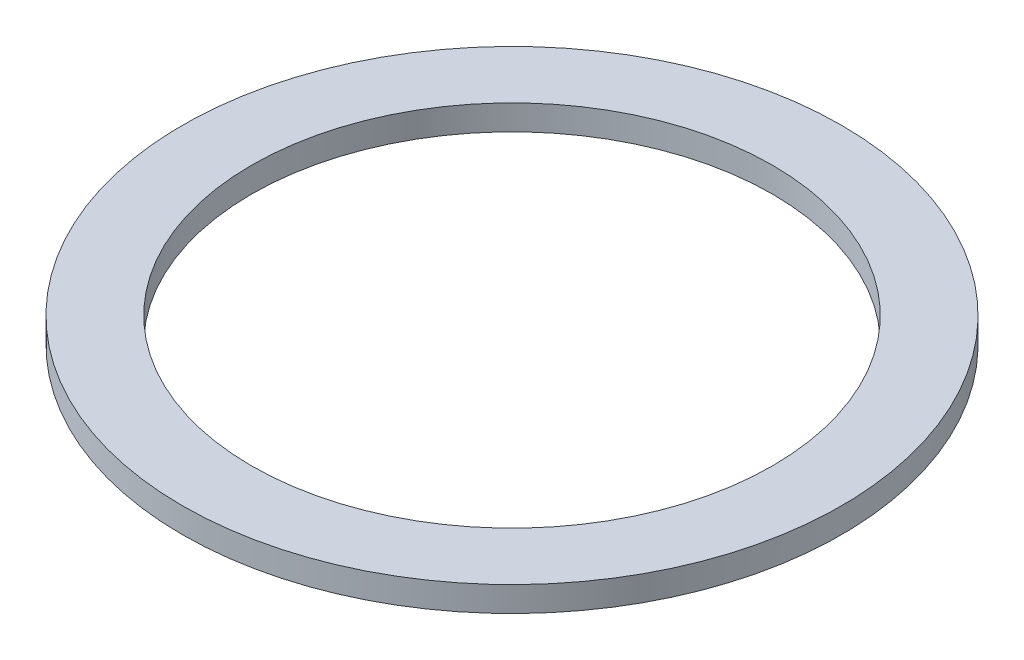
SolidWorks part; units mm, degrees
material "Copper"
ref_plane "Front Plane" through (0, 0, 0) normal (0, 0, 1) x (1, 0, 0)
ref_plane "Top Plane" through (0, 0, 0) normal (0, 1, 0) x (1, 0, 0)
ref_plane "Right Plane" through (0, 0, 0) normal (1, 0, 0) x (0, 0, -1)
sketch "Sketch1" plane through (0, 0, 0) normal (0, 1, 0) x (1, 0, 0)
  circle A0 centre (0, 0) radius 10.55
  circle A1 centre (0, 0) radius 13.35
  dimension "D1" = 2.8
  dimension "D2" = 21.1
extrude "Boss-Extrude1" add sketch "Sketch1" along normal blind 1.016
